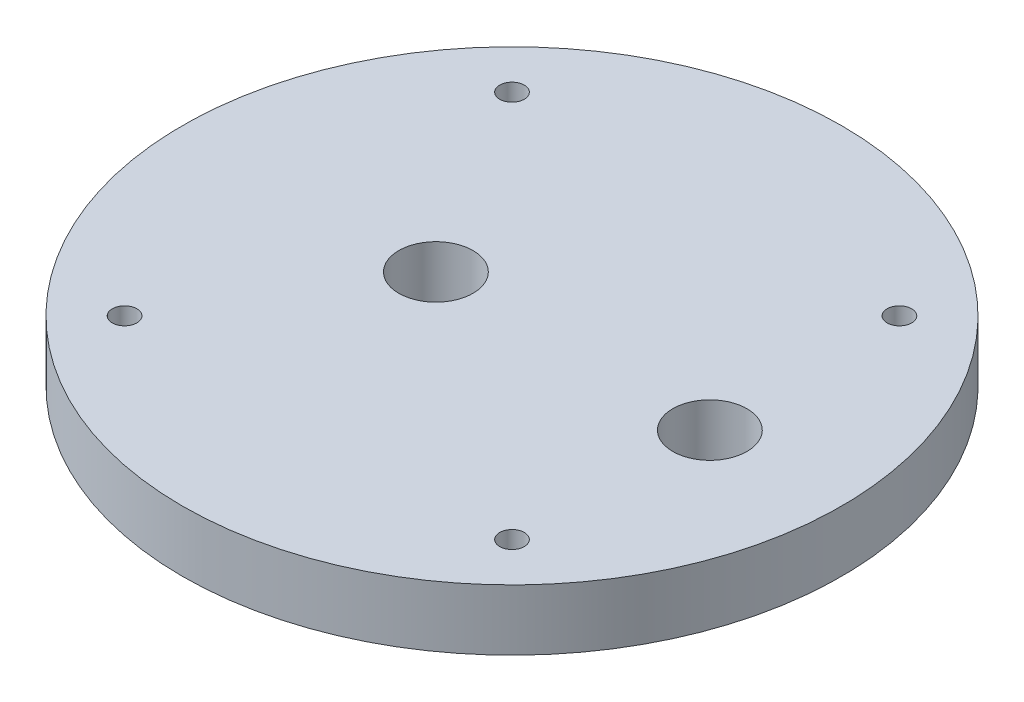
SolidWorks part; units mm, degrees
ref_plane "Front Plane" through (0, 0, 0) normal (0, 0, 1) x (1, 0, 0)
ref_plane "Top Plane" through (0, 0, 0) normal (0, 1, 0) x (1, 0, 0)
ref_plane "Right Plane" through (0, 0, 0) normal (1, 0, 0) x (0, 0, -1)
sketch "Sketch1" plane through (0, 0, 0) normal (0, 1, 0) x (1, 0, 0)
  circle A0 centre (0, 0) radius 27.5
  dimension "D1" = 55
extrude "Boss-Extrude1" add sketch "Sketch1" along normal blind 5.08
sketch "Sketch2" plane through (0, 5.08, 0) normal (0, 1, 0) x (1, 0, 0)
  line L0 (0, 0) -> (16.1645, 16.1645)
  circle A0 centre (16.1645, 16.1645) radius 1.025
  circle A1 centre (16.1645, -16.1645) radius 1.025
  circle A2 centre (-16.1645, -16.1645) radius 1.025
  circle A3 centre (-16.1645, 16.1645) radius 1.025
  point P13 (0, 0)
  dimension "D2" = 2.05
  dimension "D1" = 22.86
  dimension "D3" = 4
extrude "Cut-Extrude1" cut sketch "Sketch2" against normal blind 3.175
sketch "Sketch3" plane through (0, 5.08, 0) normal (0, 1, 0) x (1, 0, 0)
  circle A0 centre (-6.35, 0) radius 3.095
  circle A1 centre (16.51, 0) radius 3.095
  point P5 (0, 0)
  dimension "D2" = 6.19
  dimension "D3" = 6.19
  dimension "D1" = 22.86
extrude "Cut-Extrude2" cut sketch "Sketch3" against normal through all
